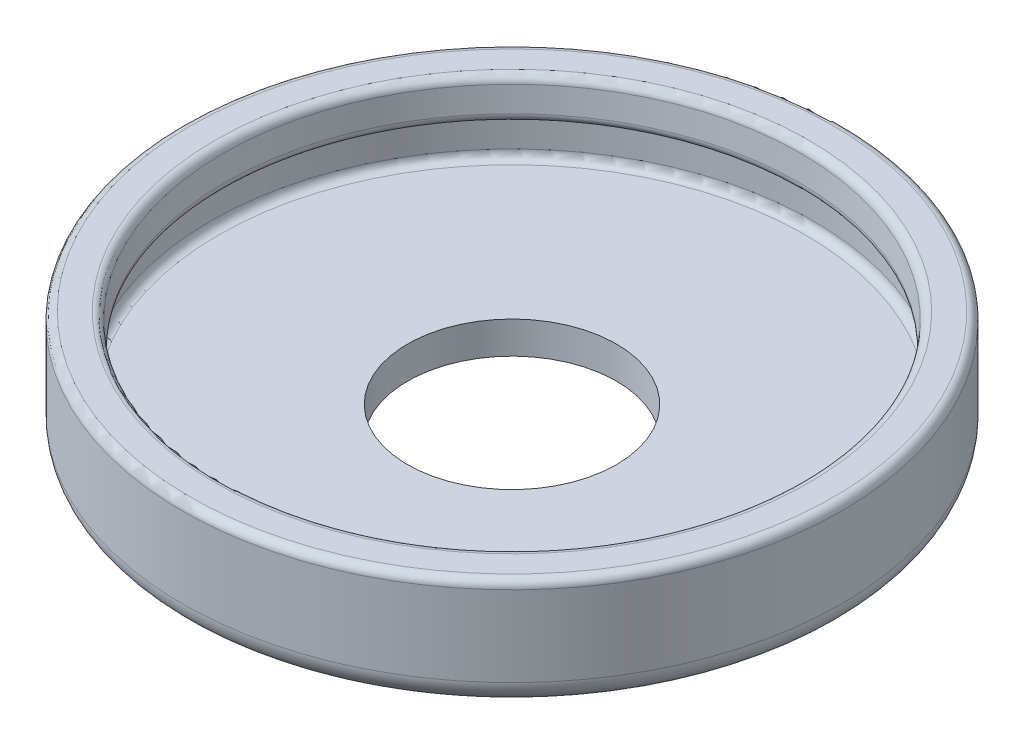
SolidWorks part; units mm, degrees
ref_plane "Front" through (0, 0, 0) normal (0, 0, 1) x (1, 0, 0)
ref_plane "Top" through (0, 0, 0) normal (0, 1, 0) x (1, 0, 0)
ref_plane "Right" through (0, 0, 0) normal (1, 0, 0) x (0, 0, -1)
sketch "Sketch1" plane through (0, 0, 0) normal (0, 0, 1) x (1, 0, 0)
  line L0 (0, -28.2916) -> (0, 1386.2876) construction
  line L1 (-28.2916, 0) -> (1386.2876, 0) construction
  line L2 (1.651, 0) -> (5.207, 0)
  line L3 (5.207, 0) -> (5.207, 1.778)
  line L4 (5.207, 1.778) -> (4.572, 1.778)
  line L5 (4.572, 1.778) -> (4.5212, 1.143)
  line L6 (4.5212, 1.143) -> (4.7625, 1.143)
  line L7 (4.7625, 1.143) -> (4.7625, 0.508)
  line L8 (4.7625, 0.508) -> (1.651, 0.508)
  line L9 (1.651, 0.508) -> (1.651, 0)
  dimension "D1" = 3.302
  dimension "D2" = 10.414
  dimension "D3" = 1.778
  dimension "D4" = 0.635
  dimension "D5" = 9.525
  dimension "D6" = 9.0424
  dimension "D7" = 0.508
  dimension "D8" = 0.635
revolve "Revolve1" add sketch "Sketch1" angle 360 about L0
fillet "Fillet1" radius 0.381 1 edges at (5.207, 0, 0)
fillet "Fillet2" radius 0.127 4 edges at (4.7625, 0.508, 0) (4.5212, 1.143, 0) (4.572, 1.778, 0) (5.207, 1.778, 0)
